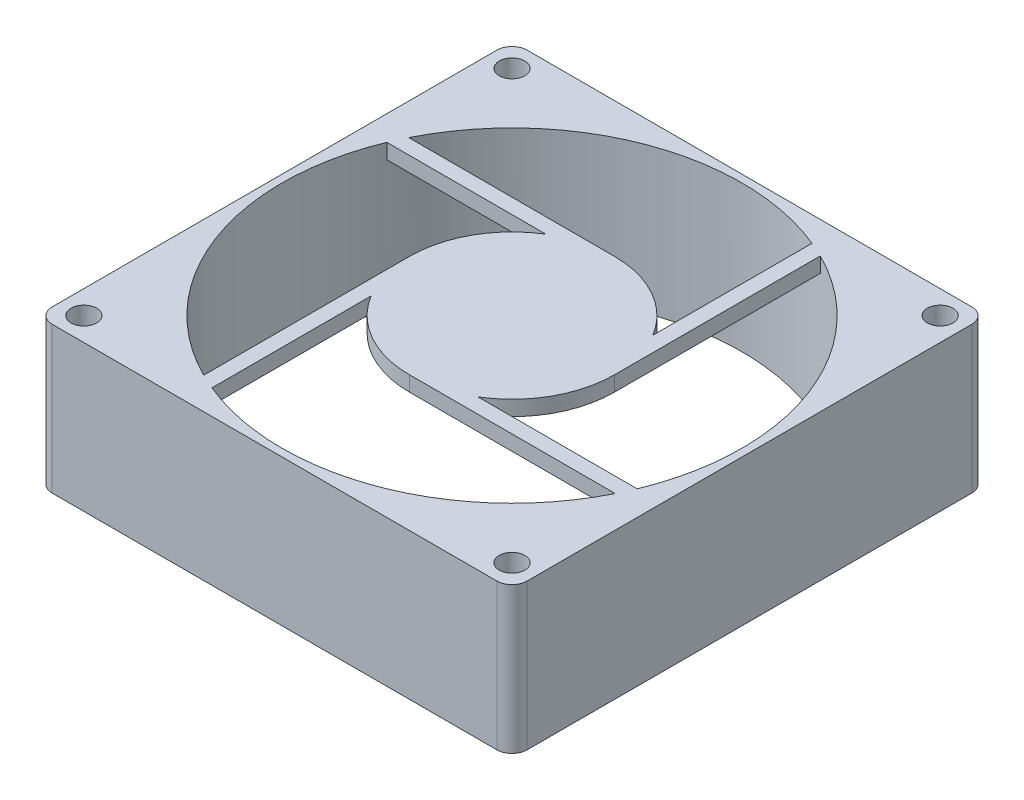
SolidWorks part; units mm, degrees
ref_plane "Front Plane" through (0, 0, 0) normal (0, 0, 1) x (1, 0, 0)
ref_plane "Top Plane" through (0, 0, 0) normal (0, 1, 0) x (1, 0, 0)
ref_plane "Right Plane" through (0, 0, 0) normal (1, 0, 0) x (0, 0, -1)
sketch "Sketch1" plane through (0, 0, 0) normal (0, 1, 0) x (1, 0, 0)
  line L1 (-40.005, -40.005) -> (40.005, -40.005)
  line L2 (-40.005, -40.005) -> (-40.005, 40.005)
  line L3 (-40.005, 40.005) -> (40.005, 40.005)
  line L4 (40.005, -40.005) -> (40.005, 40.005)
  line L5 (-40.005, -40.005) -> (40.005, 40.005) construction
  line L6 (-40.005, 40.005) -> (40.005, -40.005) construction
  point P0 (0, 0)
  dimension "D1" = 80.01
extrude "Boss-Extrude1" add sketch "Sketch1" along normal blind 24.638
sketch "Sketch2" plane through (0, 24.638, 0) normal (0, 1, 0) x (1, 0, 0)
  line L0 (40.005, 40.005) -> (-40.005, 40.005) construction
  line L1 (-40.005, 40.005) -> (-40.005, -40.005) construction
  line L2 (40.005, -40.005) -> (40.005, 40.005) construction
  circle A0 centre (0, 0) radius 38.735
  circle A1 centre (-36.068, 36.068) radius 2.159
  circle A2 centre (36.068, 36.068) radius 2.159
  circle A3 centre (36.068, -36.068) radius 2.159
  circle A4 centre (-36.068, -36.068) radius 2.159
  point P18 (0, 0)
  dimension "D1" = 4.318
  dimension "D4" = 77.47
  dimension "D2" = 3.937
  dimension "D3" = 3.937
  dimension "D6" = 3.937
  dimension "D7" = 3.937
  dimension "D5" = 4
extrude "Cut-Extrude1" cut sketch "Sketch2" against normal blind 24.638
fillet "Fillet1" radius 2.54 4 edges at (40.005, 12.319, 40.005) (40.005, 12.319, -40.005) (-40.005, 12.319, 40.005) (-40.005, 12.319, -40.005)
sketch "Sketch3" plane through (0, 24.638, 0) normal (0, 1, 0) x (1, 0, 0)
  line L0 (17.272, 0) -> (17.272, 34.671)
  line L1 (14.732, 9.0161) -> (14.732, 35.8241)
  line L2 (14.732, 0) -> (14.732, 34.671) construction
  line L3 (0, -17.272) -> (34.671, -17.272)
  line L4 (9.0161, -14.732) -> (35.8241, -14.732)
  line L5 (-17.272, 0) -> (-17.272, -34.671)
  line L6 (-14.732, -9.0161) -> (-14.732, -35.8241)
  line L7 (0, 17.272) -> (-34.671, 17.272)
  line L8 (-9.0161, 14.732) -> (-35.8241, 14.732)
  arc A0 (-14.732, -9.0161) -> (0, -17.272) centre (0, 0) ccw
  circle A1 centre (0, 0) radius 38.735 construction
  arc A3 (34.671, -17.272) -> (35.8241, -14.732) centre (0, 0) ccw
  arc A4 (-9.0161, 14.732) -> (-17.272, 0) centre (0, 0) ccw
  arc A5 (14.732, 9.0161) -> (0, 17.272) centre (0, 0) ccw
  arc A6 (9.0161, -14.732) -> (17.272, 0) centre (0, 0) ccw
  arc A7 (17.272, 34.671) -> (14.732, 35.8241) centre (0, 0) ccw
  arc A8 (-34.671, 17.272) -> (-35.8241, 14.732) centre (0, 0) ccw
  arc A9 (-17.272, -34.671) -> (-14.732, -35.8241) centre (0, 0) ccw
  point P27 (0, 0)
  dimension "D1" = 34.544
  dimension "D2" = 2.54
  dimension "D3" = 4
extrude "Boss-Extrude2" add sketch "Sketch3" against normal blind 2.54
